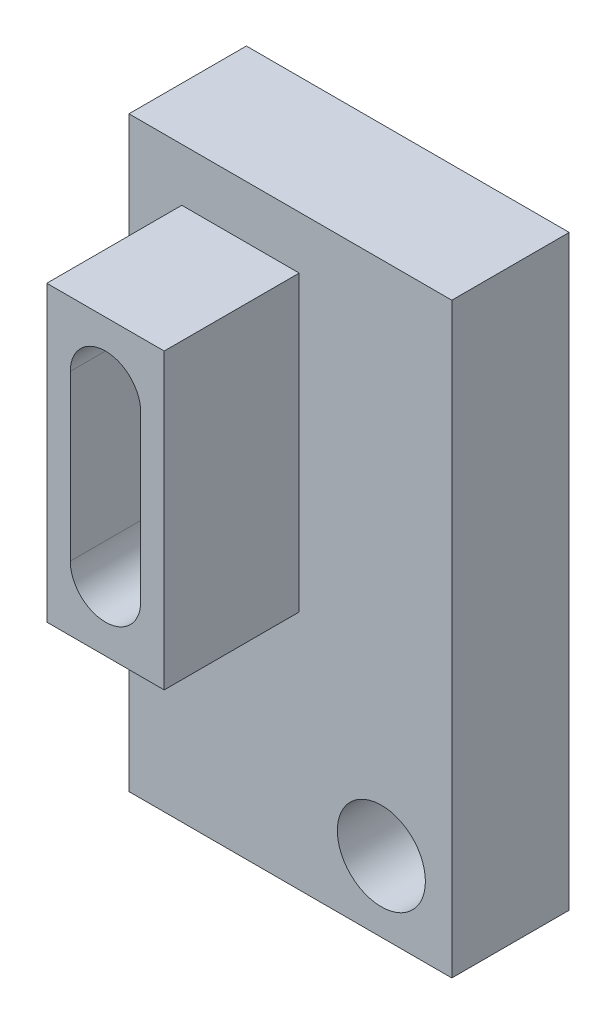
SolidWorks part; units mm, degrees
ref_plane "Спереди" through (0, 0, 0) normal (0, 0, 1) x (1, 0, 0)
ref_plane "Сверху" through (0, 0, 0) normal (0, 1, 0) x (1, 0, 0)
ref_plane "Справа" through (0, 0, 0) normal (1, 0, 0) x (0, 0, -1)
sketch "Эскиз1" plane through (0, 0, 0) normal (0, 0, 1) x (1, 0, 0)
  line L1 (-27.5, -50) -> (27.5, -50)
  line L2 (-27.5, -50) -> (-27.5, 50)
  line L3 (-27.5, 50) -> (27.5, 50)
  line L4 (27.5, -50) -> (27.5, 50)
  line L5 (-27.5, -50) -> (27.5, 50) construction
  line L6 (-27.5, 50) -> (27.5, -50) construction
  point P0 (0, 0)
  dimension "D1" = 55
  dimension "D2" = 100
extrude "Бобышка-Вытянуть1" add sketch "Эскиз1" along normal blind 20
sketch "Эскиз2" plane through (0, 0, 20) normal (0, 0, 1) x (1, 0, 0)
  line L0 (-27.5, -50) -> (27.5, -50) construction
  line L1 (27.5, -50) -> (27.5, 50) construction
  circle A0 centre (15.5, -38) radius 7.5
  dimension "D2" = 12
  dimension "D3" = 15
  dimension "D1" = 12
extrude "Вырез-Вытянуть1" cut sketch "Эскиз2" against normal through all
sketch "Эскиз3" plane through (0, 0, 20) normal (0, 0, 1) x (1, 0, 0)
  line L0 (27.5, 50) -> (-27.5, 50) construction
  line L1 (-18.5, -9) -> (1.5, -9)
  line L2 (-18.5, -9) -> (-18.5, 41)
  line L3 (-18.5, 41) -> (1.5, 41)
  line L4 (1.5, -9) -> (1.5, 41)
  line L5 (-18.5, -9) -> (1.5, 41) construction
  line L6 (-18.5, 41) -> (1.5, -9) construction
  line L7 (-27.5, 50) -> (-27.5, -50) construction
  point P0 (-8.5, 16)
  dimension "D1" = 9
  dimension "D2" = 9
  dimension "D3" = 20
  dimension "D4" = 50
extrude "Бобышка-Вытянуть2" add sketch "Эскиз3" along normal blind 23
sketch "Эскиз4" plane through (0, 0, 43) normal (0, 0, 1) x (1, 0, 0)
  line L0 (-8.5, 41) -> (-8.5, -9) construction
  line L1 (1.5, 41) -> (-18.5, 41) construction
  line L2 (-18.5, -9) -> (1.5, -9) construction
  line L3 (-8.5, 2) -> (-8.5, 30) construction
  line L4 (-14.5, 2) -> (-14.5, 30)
  line L5 (-2.5, 2) -> (-2.5, 30)
  arc A0 (-14.5, 2) -> (-2.5, 2) centre (-8.5, 2) ccw
  arc A1 (-2.5, 30) -> (-14.5, 30) centre (-8.5, 30) ccw
  point P8 (-8.5, 16)
  dimension "D2" = 40
  dimension "D1" = 12
extrude "Вырез-Вытянуть2" cut sketch "Эскиз4" against normal through all
